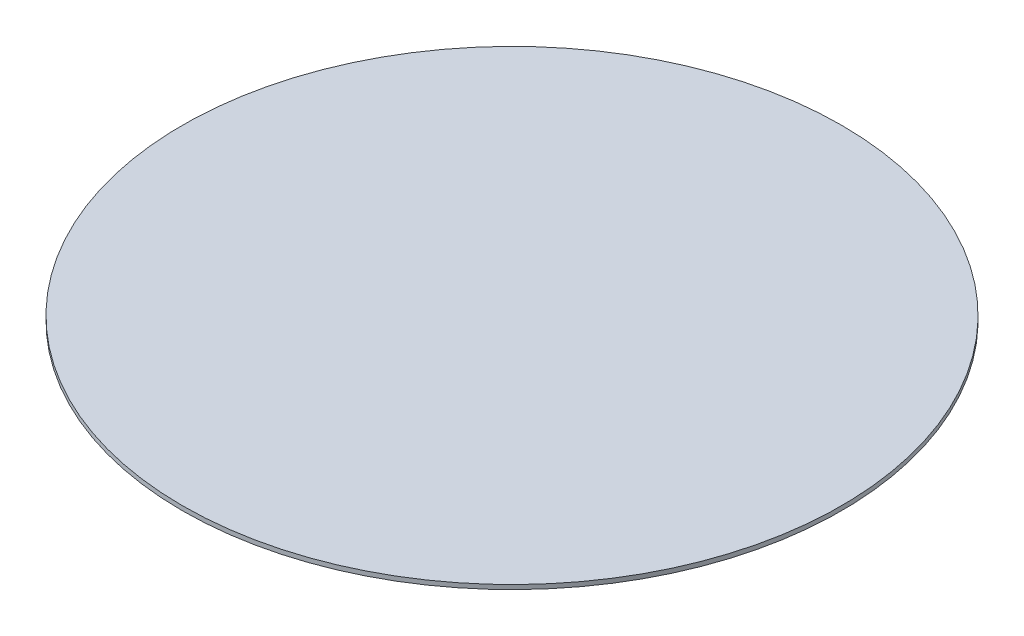
SolidWorks part; units mm, degrees
ref_plane "Front Plane" through (0, 0, 0) normal (0, 0, 1) x (1, 0, 0)
ref_plane "Top Plane" through (0, 0, 0) normal (0, 1, 0) x (1, 0, 0)
ref_plane "Right Plane" through (0, 0, 0) normal (1, 0, 0) x (0, 0, -1)
sketch "Sketch1" plane through (0, 0, 0) normal (0, 1, 0) x (1, 0, 0)
  circle A0 centre (0, 0) radius 60
  dimension "D1" = 120
extrude "Boss-Extrude1" add sketch "Sketch1" along normal blind 0.8
